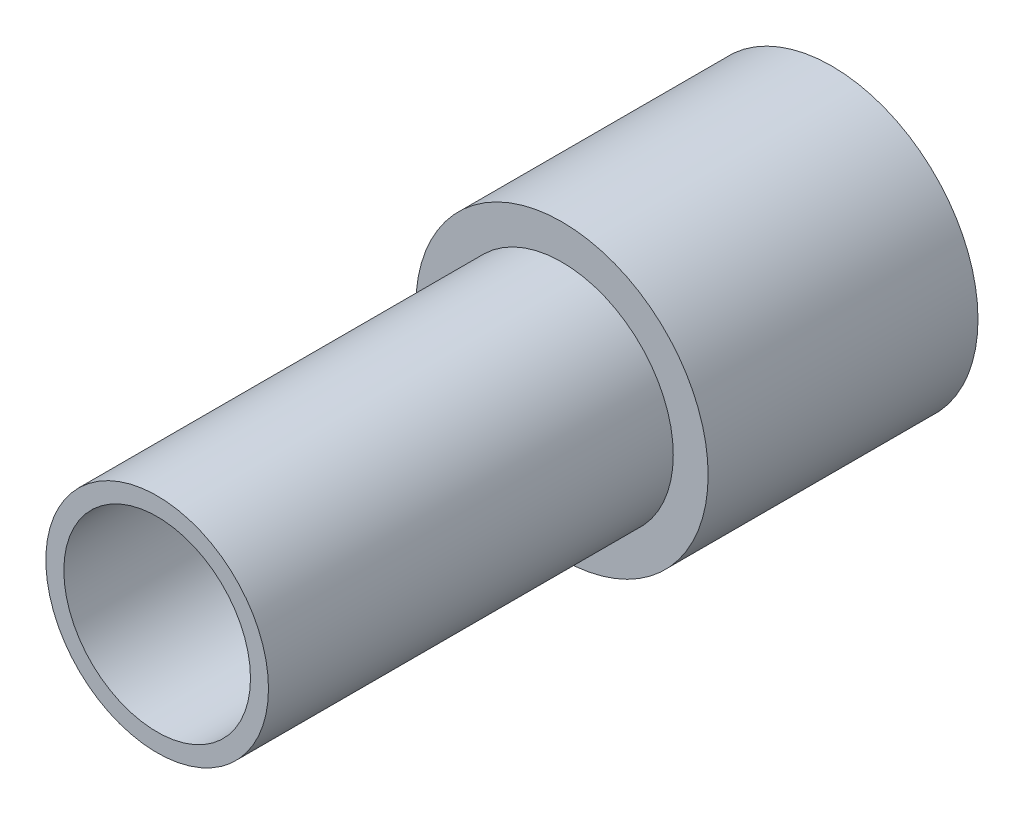
SolidWorks part; units mm, degrees
ref_plane "Front Plane" through (0, 0, 0) normal (0, 0, 1) x (1, 0, 0)
ref_plane "Top Plane" through (0, 0, 0) normal (0, 1, 0) x (1, 0, 0)
ref_plane "Right Plane" through (0, 0, 0) normal (1, 0, 0) x (0, 0, -1)
sketch "Sketch1" plane through (0, 0, 0) normal (0, 0, 1) x (1, 0, 0)
  circle A0 centre (0, 0) radius 6.5
  circle A1 centre (0, 0) radius 4.15
  dimension "D1" = 13
  dimension "D2" = 8.3
extrude "Boss-Extrude1" add sketch "Sketch1" along normal blind 30
sketch "Sketch2" plane through (0, 0, 30) normal (0, 0, 1) x (1, 0, 0)
  circle A0 centre (0, 0) radius 4.95
  circle A1 centre (0, 0) radius 6.5
  circle A2 centre (0, 0) radius 6.5 construction
  dimension "D1" = 9.9
extrude "Cut-Extrude1" cut sketch "Sketch2" against normal blind 18
